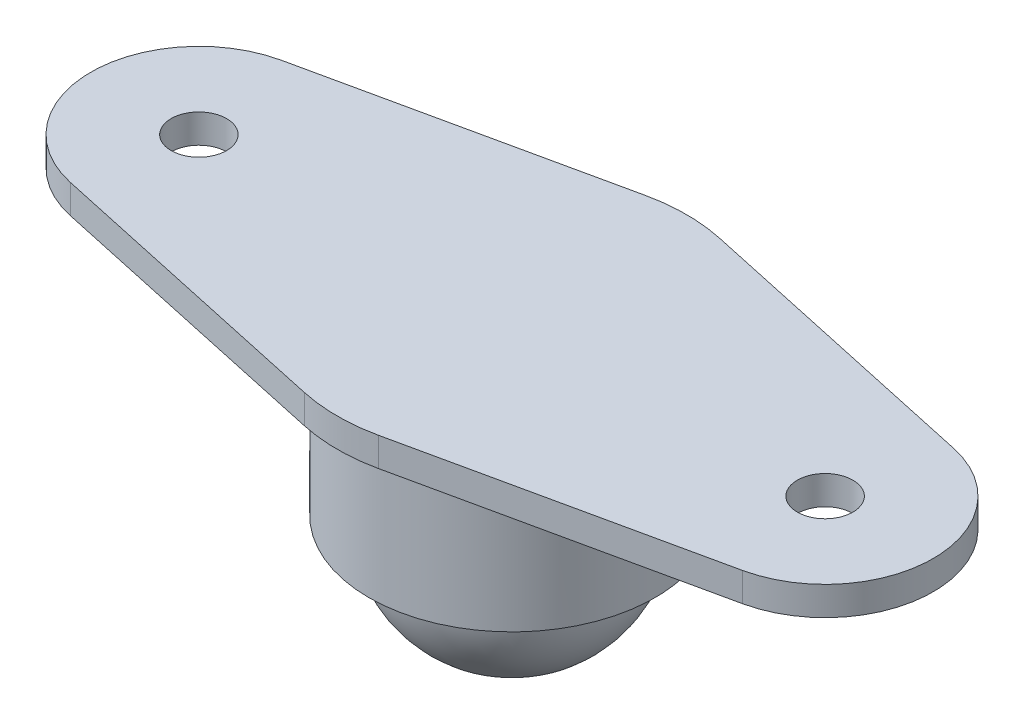
SolidWorks part; units mm, degrees
ref_plane "Front Plane" through (0, 0, 0) normal (0, 0, 1) x (1, 0, 0)
ref_plane "Top Plane" through (0, 0, 0) normal (0, 1, 0) x (1, 0, 0)
ref_plane "Right Plane" through (0, 0, 0) normal (1, 0, 0) x (0, 0, -1)
sketch "Sketch1" plane through (0, 0, 0) normal (0, 1, 0) x (1, 0, 0)
  line L0 (-23.3119, 7.3291) -> (-2.5703, 11.8341)
  line L1 (0, 0) -> (0, 8.2317) construction
  line L2 (-23.3119, -7.3291) -> (-2.5703, -11.8341)
  line L3 (5.4356, 0) -> (0, 0) construction
  line L4 (23.3119, -7.3291) -> (2.5703, -11.8341)
  line L5 (23.3119, 7.3291) -> (2.5703, 11.8341)
  arc A0 (2.5703, 11.8341) -> (-2.5703, 11.8341) centre (0, 0) ccw
  arc A1 (-23.3119, 7.3291) -> (-23.3119, -7.3291) centre (-21.72, 0) ccw
  arc A2 (23.3119, 7.3291) -> (23.3119, -7.3291) centre (21.72, 0) cw
  arc A3 (-2.5703, -11.8341) -> (2.5703, -11.8341) centre (0, 0) ccw
  circle A4 centre (-21.72, 0) radius 1.925
  circle A5 centre (21.72, 0) radius 1.925
  dimension "D1" = 24.22
  dimension "D3" = 15
  dimension "D4" = 3.85
  dimension "D2" = 21.72
extrude "Boss-Extrude1" add sketch "Sketch1" along normal blind 2
sketch "Sketch2" plane through (0, 0, 0) normal (1, 0, 0) x (0, 0, -1)
  line L0 (7.3291, 2) -> (-7.3291, 2) construction
  line L1 (0, -2.15) -> (0, -18)
  arc A0 (0, -18) -> (0, -2.15) centre (0, -10.075) ccw
  dimension "D1" = 7.925
  dimension "D2" = 12.075
revolve "Revolve2" add sketch "Sketch2" angle 360 about L1
sketch "Sketch3" plane through (0, 0, 0) normal (0, -1, 0) x (1, 0, 0)
  circle A0 centre (0, 0) radius 7.925
  circle A1 centre (0, 0) radius 9.925
  dimension "D1" = 2
extrude "Boss-Extrude2" add sketch "Sketch3" along normal blind 10
